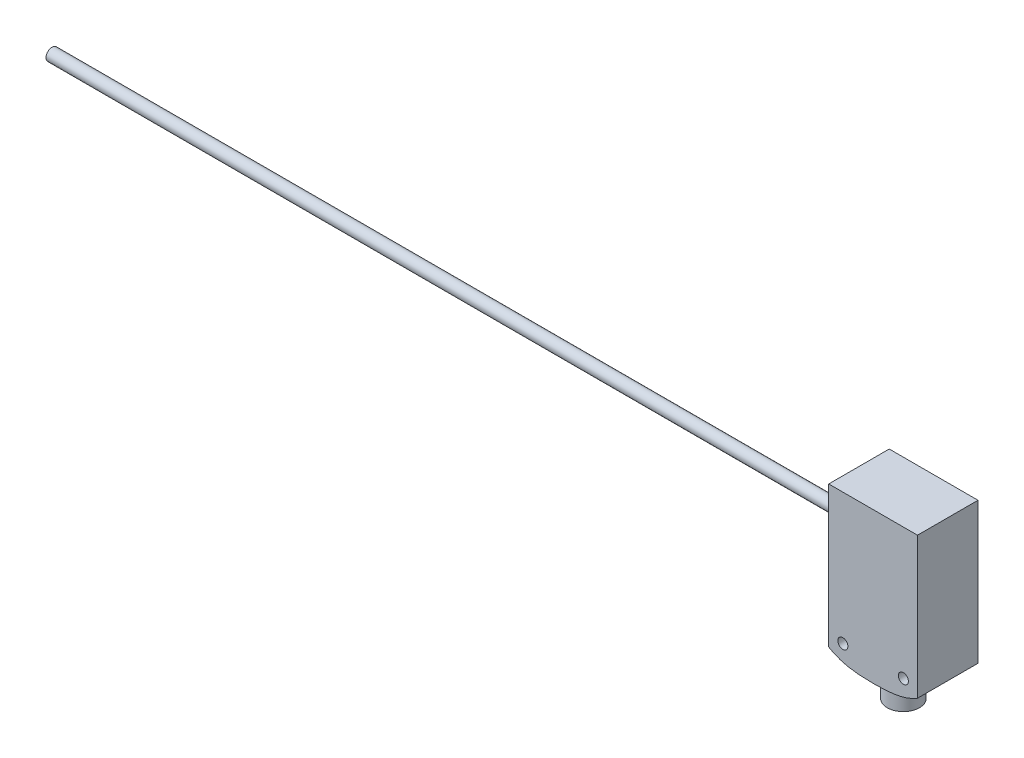
SolidWorks part; units mm, degrees
ref_plane "Plan de face" through (0, 0, 0) normal (0, 0, 1) x (1, 0, 0)
ref_plane "Plan de dessus" through (0, 0, 0) normal (0, 1, 0) x (1, 0, 0)
ref_plane "Plan de droite" through (0, 0, 0) normal (1, 0, 0) x (0, 0, -1)
sketch "Esquisse1" plane through (0, 0, 0) normal (0, 0, 1) x (1, 0, 0)
  line L0 (0, 0) -> (0, 44.3) construction
  line L1 (-11, 0) -> (11, 0)
  line L2 (11, 0) -> (11, 44.3)
  line L3 (11, 44.3) -> (-11, 44.3)
  line L4 (-11, 0) -> (-11, 44.3)
  circle A0 centre (7.5, 11.8) radius 1.25
  circle A1 centre (-7.5, 11.8) radius 1.25
  dimension "D3" = 2.5
  dimension "D4" = 11.8
  dimension "D5" = 15
  dimension "D1" = 22
  dimension "D2" = 44.3
extrude "Boss.-Extru.1" add sketch "Esquisse1" along normal blind 15
sketch "Esquisse2" plane through (0, 0, 15) normal (0, 0, 1) x (1, 0, 0)
  line L0 (0, 0) -> (0, 44.3) construction
  line L1 (-11, 0) -> (11, 0) construction
  line L2 (11, 44.3) -> (-11, 44.3) construction
  line L3 (11, 0) -> (11, 44.3) construction
  line L4 (-11, 9.3) -> (-11, 0)
  line L5 (-11, 0) -> (11, 0)
  line L6 (11, 0) -> (11, 9.3)
  spline S0 degree 3 poles (-11, 9.3) (-7.6254, 7.2367) (0, 6.7633) (7.6254, 7.2367) (11, 9.3) knots 0 0 0 0 0.5 1 1 1 1
  point P6 (0, 7)
  point P7 (11, 9.3)
  point P8 (5.8, 7.4)
  point P11 (-5.8, 7.4)
  point P12 (-11, 9.3)
  dimension "D1" = 37.3
  dimension "D2" = 35
  dimension "D3" = 36.9
  dimension "D4" = 5.8
extrude "Enlèv. mat.-Extru.1" cut sketch "Esquisse2" against normal through all
sketch "Esquisse3" plane through (0, 0, 0) normal (0, 1, 0) x (1, 0, 0)
  line L0 (11, 0) -> (-11, -15) construction
  circle A0 centre (0, -7.5) radius 4
  dimension "D1" = 8
extrude "Boss.-Extru.2" add sketch "Esquisse3" along normal up to next
sketch "Esquisse4" plane through (-11, 0, 0) normal (-1, 0, 0) x (0, 0, 1)
  line L0 (7.5, 44.3) -> (7.5, 9.3) construction
  line L1 (15, 44.3) -> (0, 44.3) construction
  line L2 (0, 9.3) -> (15, 9.3) construction
  line L3 (1.3, 37.8) -> (13.7, 37.8)
  line L4 (13.7, 37.8) -> (13.7, 16.8)
  line L5 (15, 44.3) -> (15, 9.3) construction
  line L6 (1.3, 37.8) -> (1.3, 16.8)
  arc A0 (1.3, 16.8) -> (13.7, 16.8) centre (7.5, 35.8147) ccw
  point P13 (7.5, 37.8)
  dimension "D3" = 20
  dimension "D1" = 6.5
  dimension "D2" = 1.3
  dimension "D4" = 21
extrude "Enlèv. mat.-Extru.2" cut sketch "Esquisse4" against normal blind 0.1
sketch "Esquisse5" plane through (-11, 0, 0) normal (-1, 0, 0) x (0, 0, 1)
  line L0 (7.5, 37.8) -> (7.5, 9.3) construction
  line L1 (13.7, 37.8) -> (1.3, 37.8) construction
  line L2 (0, 9.3) -> (15, 9.3) construction
  circle A0 centre (7.5, 32.8) radius 1.5
  dimension "D1" = 3
  dimension "D2" = 5
extrude "Boss.-Extru.3" add sketch "Esquisse5" along normal blind 200 separate body
